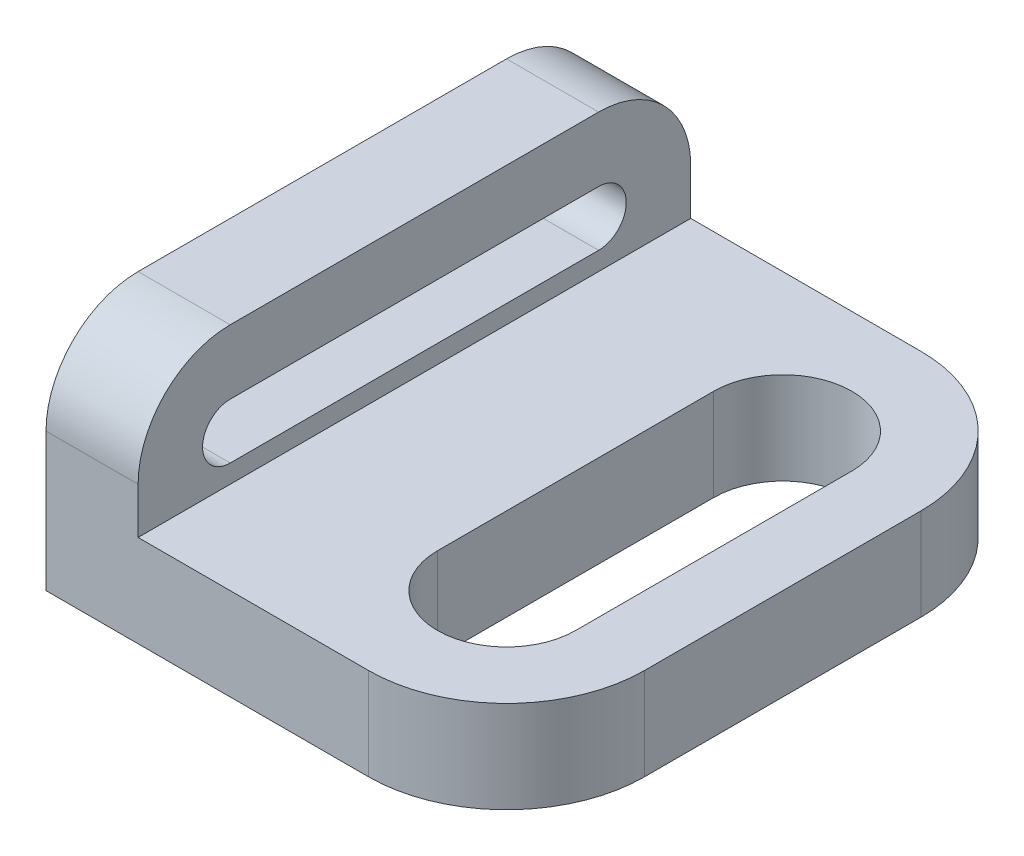
SolidWorks part; units mm, degrees
ref_plane "Front Plane" through (0, 0, 0) normal (0, 0, 1) x (1, 0, 0)
ref_plane "Top Plane" through (0, 0, 0) normal (0, 1, 0) x (1, 0, 0)
ref_plane "Right Plane" through (0, 0, 0) normal (1, 0, 0) x (0, 0, -1)
sketch "Sketch2" plane through (0, 0, 0) normal (0, 1, 0) x (1, 0, 0)
  line L0 (20, 30) -> (20, -30) construction
  line L1 (-50, 60) -> (50, 60)
  line L2 (-50, 60) -> (-50, -60)
  line L3 (-50, -60) -> (50, -60)
  line L4 (50, 60) -> (50, -60)
  line L5 (-50, 60) -> (50, -60) construction
  line L6 (-50, -60) -> (50, 60) construction
  line L7 (35, 30) -> (35, -30)
  line L8 (5, 30) -> (5, -30)
  arc A0 (35, 30) -> (5, 30) centre (20, 30) ccw
  arc A1 (5, -30) -> (35, -30) centre (20, -30) ccw
  point P0 (0, 0)
  point P8 (20, 0)
  dimension "D1" = 100
  dimension "D2" = 120
  dimension "D3" = 70
  dimension "D4" = 60
  dimension "D5" = 30
  dimension "D6" = 15
extrude "Boss-Extrude1" add sketch "Sketch2" along normal blind 20
fillet "Fillet1" radius 30 1 edges at (50, 10, -60)
fillet "Fillet2" radius 30 1 edges at (50, 10, 60)
sketch "Sketch3" plane through (0, 20, 0) normal (0, 1, 0) x (1, 0, 0)
  line L0 (20, 60) -> (-50, 60) construction
  line L1 (-50, 60) -> (-30, 60)
  line L2 (-50, 60) -> (-50, -60)
  line L3 (-50, -60) -> (-30, -60)
  line L4 (-30, 60) -> (-30, -60)
  line L5 (-50, 60) -> (-30, -60) construction
  line L6 (-50, -60) -> (-30, 60) construction
  line L7 (-50, -60) -> (20, -60) construction
  line L8 (-50, 60) -> (-50, -60) construction
  point P0 (-40, 0)
  dimension "D1" = 20
extrude "Boss-Extrude2" add sketch "Sketch3" along normal blind 30
sketch "Sketch4" plane through (-30, 0, 0) normal (1, 0, 0) x (0, 0, -1)
  line L0 (-40, 30) -> (40, 30) construction
  line L1 (-40, 36) -> (40, 36)
  line L2 (-40, 24) -> (40, 24)
  line L3 (-60, 50) -> (-60, 20) construction
  line L4 (30, 0) -> (60, 0) construction
  arc A0 (-40, 36) -> (-40, 24) centre (-40, 30) ccw
  arc A1 (40, 24) -> (40, 36) centre (40, 30) ccw
  point P2 (0, 30)
  point P11 (1.7135, 56.5432)
  dimension "D1" = 6
  dimension "D2" = 20
  dimension "D3" = 80
  dimension "D4" = 30
extrude "Cut-Extrude1" cut sketch "Sketch4" against normal up to surface (20 mm away) up to face at (-50, 25, 0)
fillet "Fillet3" radius 20 2 edges at (-40, 50, 60) (-40, 50, -60)
